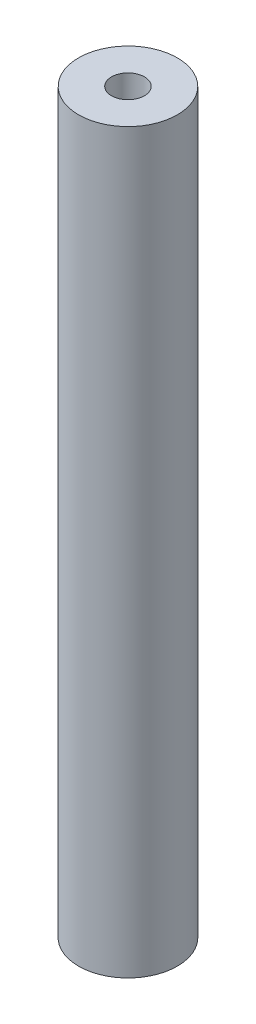
SolidWorks part; units mm, degrees
ref_plane "Front Plane" through (0, 0, 0) normal (0, 0, 1) x (1, 0, 0)
ref_plane "Top Plane" through (0, 0, 0) normal (0, 1, 0) x (1, 0, 0)
ref_plane "Right Plane" through (0, 0, 0) normal (1, 0, 0) x (0, 0, -1)
sketch "Sketch1" plane through (0, 0, 0) normal (0, 1, 0) x (1, 0, 0)
  circle A0 centre (0, 0) radius 47.625
  circle A1 centre (0, 0) radius 15.875
  dimension "D1" = 95.25
  dimension "D2" = 31.75
extrude "Boss-Extrude1" add sketch "Sketch1" along normal mid plane 711.2
